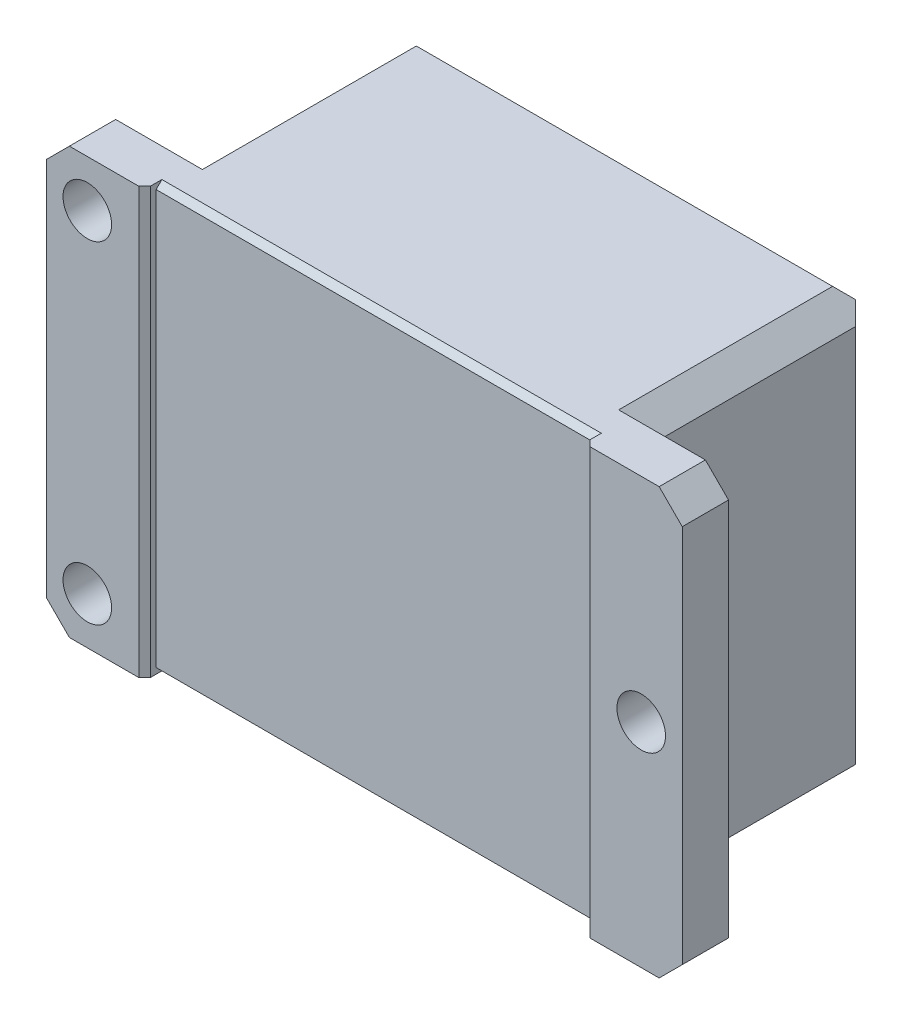
SolidWorks part; units mm, degrees
ref_plane "前视基准面" through (0, 0, 0) normal (0, 0, 1) x (1, 0, 0)
ref_plane "上视基准面" through (0, 0, 0) normal (0, 1, 0) x (1, 0, 0)
ref_plane "右视基准面" through (0, 0, 0) normal (1, 0, 0) x (0, 0, -1)
sketch "草图1" plane through (0, 0, 0) normal (0, 0, 1) x (1, 0, 0)
  line L1 (0, 0) -> (-55, 0)
  line L2 (0, 0) -> (0, 36.8)
  line L3 (0, 36.8) -> (-55, 36.8)
  line L4 (-55, 0) -> (-55, 36.8)
  line L5 (0, 0) -> (-55, 36.8) construction
  line L6 (0, 36.8) -> (-55, 0) construction
  point P4 (-27.5, 18.4)
  dimension "D1" = 36.8
  dimension "D2" = 55
extrude "凸台-拉伸1" add sketch "草图1" along normal blind 24
sketch "草图2" plane through (0, 0, 24) normal (0, 0, 1) x (1, 0, 0)
  line L0 (-27.5, 36.8) -> (-27.5, 18.4) construction
  line L1 (-8.5, 0) -> (-46.5, 0)
  line L2 (-8.5, 0) -> (-8.5, 36.8)
  line L3 (-8.5, 36.8) -> (-46.5, 36.8)
  line L4 (-46.5, 0) -> (-46.5, 36.8)
  line L5 (-8.5, 0) -> (-46.5, 36.8) construction
  line L6 (-8.5, 36.8) -> (-46.5, 0) construction
  line L7 (0, 36.8) -> (-55, 36.8) construction
  line L9 (-55, 0) -> (0, 0) construction
  point P0 (-27.5, 18.4)
  dimension "D1" = 38
extrude "切除-拉伸1" cut sketch "草图2" against normal blind 1
chamfer "倒角1" distance 0.5 angle 45 2 edges at (-8.5, 18.4, 24) (-46.5, 18.4, 24)
chamfer "倒角2" distance 0.5 angle 45 2 edges at (-27.5, 0, 23) (-27.5, 36.8, 23)
sketch "草图3" plane through (0, 0, 0) normal (0, 0, -1) x (-1, 0, 0)
  line L0 (55, 0) -> (0, 0) construction
  line L1 (0, 36.8) -> (7.5, 36.8)
  line L2 (0, 36.8) -> (0, 0)
  line L3 (0, 0) -> (7.5, 0)
  line L4 (7.5, 36.8) -> (7.5, 0)
  line L5 (0, 36.8) -> (7.5, 0) construction
  line L6 (0, 0) -> (7.5, 36.8) construction
  line L8 (55, 36.8) -> (47.5, 36.8)
  line L9 (55, 36.8) -> (55, 0)
  line L10 (55, 0) -> (47.5, 0)
  line L11 (47.5, 36.8) -> (47.5, 0)
  line L12 (55, 36.8) -> (47.5, 0) construction
  line L13 (55, 0) -> (47.5, 36.8) construction
  point P4 (3.75, 18.4)
  point P12 (51.25, 18.4)
  dimension "D1" = 7.5
  dimension "D2" = 7.5
extrude "切除-拉伸2" cut sketch "草图3" against normal blind 20
chamfer "倒角3" distance 1.5 angle 45 4 edges at (-7.5, 18.4, 0) (-27.5, 36.8, 0) (-47.5, 18.4, 0) (-27.5, 0, 0)
chamfer "倒角4" distance 2 angle 45 4 edges at (-47.5, 0, 10.75) (-47.5, 36.8, 10.75) (-7.5, 36.8, 10.75) (-7.5, 0, 10.75)
chamfer "倒角5" distance 2 angle 45 4 edges at (0, 36.8, 22) (0, 0, 22) (-55, 0, 22) (-55, 36.8, 22)
sketch "草图4" plane through (0, 0, 20) normal (0, 0, -1) x (-1, 0, 0)
  line L0 (51.45, 32.75) -> (51.45, 4.05) construction
  line L1 (3.55, 18.4) -> (51.45, 18.4) construction
  line L2 (51.45, 18.4) -> (55, 18.4) construction
  line L3 (55, 2) -> (55, 34.8) construction
  line L4 (0, 34.8) -> (0, 2) construction
  circle A0 centre (3.55, 18.4) radius 2.1
  circle A2 centre (51.45, 32.75) radius 2.1
  circle A3 centre (51.45, 4.05) radius 2.1
  dimension "D1" = 4.2
  dimension "D2" = 47.9
  dimension "D4" = 28.7
  dimension "D3" = 3.55
extrude "切除-拉伸3" cut sketch "草图4" against normal blind 20
sketch "草图5" plane through (-47.5, 0, 0) normal (-1, 0, 0) x (0, 0, 1)
  line L0 (10, 18.4) -> (20, 18.4) construction
  line L1 (20, 34.8) -> (20, 2) construction
  circle A0 centre (10, 18.4) radius 5
  dimension "D1" = 10
  dimension "D2" = 10
extrude "凸台-拉伸2" add sketch "草图5" along normal blind 10
